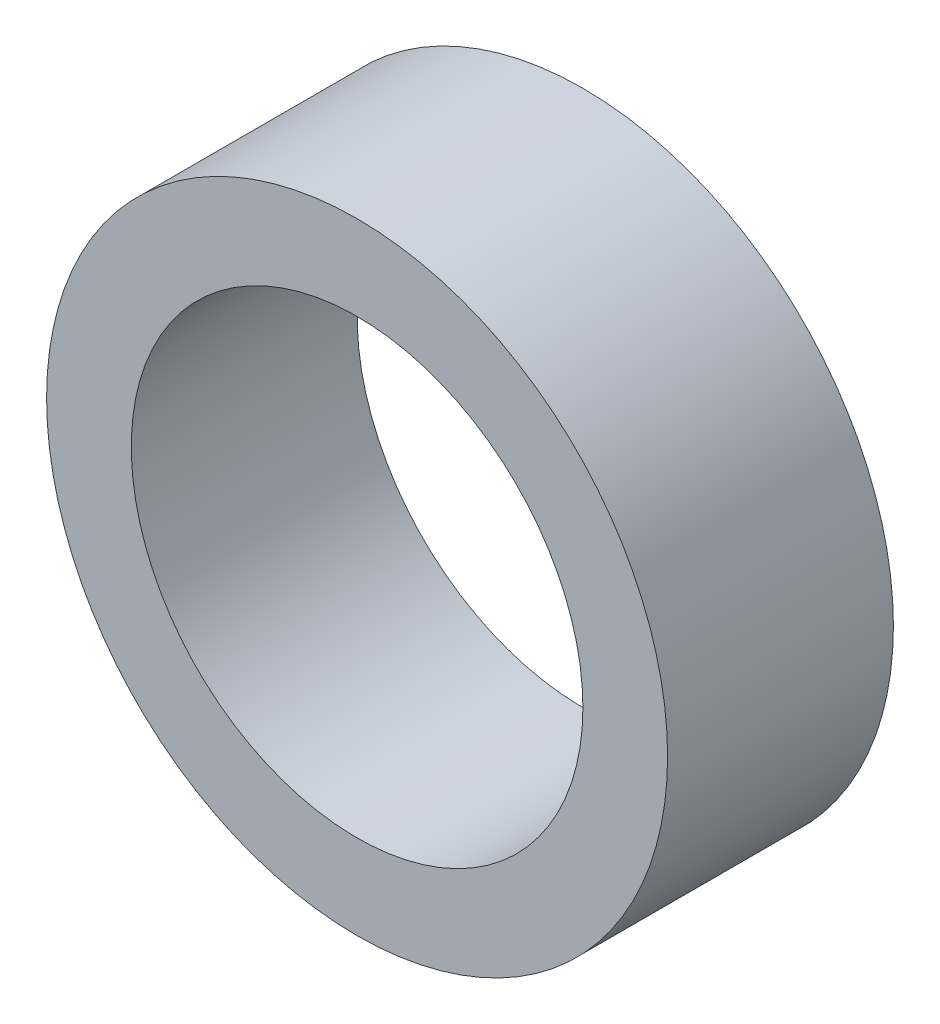
SolidWorks part; units mm, degrees
ref_plane "Спереди" through (0, 0, 0) normal (0, 0, 1) x (1, 0, 0)
ref_plane "Сверху" through (0, 0, 0) normal (0, 1, 0) x (1, 0, 0)
ref_plane "Справа" through (0, 0, 0) normal (1, 0, 0) x (0, 0, -1)
sketch "Эскиз1" plane through (0, 0, 0) normal (0, 0, 1) x (1, 0, 0)
  circle A0 centre (0, 0) radius 5.5
  dimension "D1" = 11
extrude "Основание-Вытянуть" add sketch "Эскиз1" along normal blind 4
sketch "Эскиз2" plane through (0, 0, 4) normal (0, 0, 1) x (1, 0, 0)
  circle A0 centre (0, 0) radius 4
  dimension "D1" = 8
extrude "Вырез-Вытянуть1" cut sketch "Эскиз2" against normal through all
